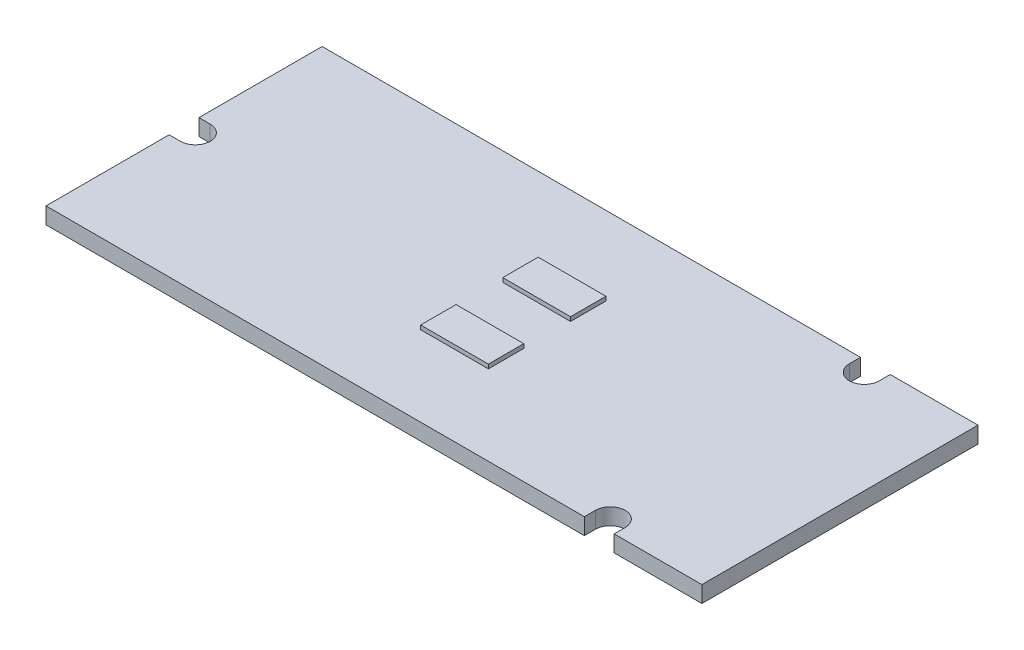
SolidWorks part; units mm, degrees
ref_plane "Front" through (0, 0, 0) normal (0, 0, 1) x (1, 0, 0)
ref_plane "Top" through (0, 0, 0) normal (0, 1, 0) x (1, 0, 0)
ref_plane "Right" through (0, 0, 0) normal (1, 0, 0) x (0, 0, -1)
sketch "Sketch1" plane through (0, 0, 0) normal (0, 1, 0) x (1, 0, 0)
  line L0 (-31.95, 0) -> (31.95, 0) construction
  line L1 (31.95, -13.45) -> (23.4, -13.45)
  line L2 (31.95, -13.45) -> (31.95, 13.45)
  line L3 (31.95, 13.45) -> (23.4, 13.45)
  line L4 (-31.95, -13.45) -> (-31.95, -1.45)
  line L5 (31.95, -13.45) -> (-31.95, 13.45) construction
  line L6 (31.95, 13.45) -> (-31.95, -13.45) construction
  line L7 (21.95, 13.7097) -> (21.95, -13.45) construction
  line L8 (20.5, 12.375) -> (20.5, 13.45)
  line L9 (23.4, 12.375) -> (23.4, 13.45)
  line L10 (20.5, 13.45) -> (-31.95, 13.45)
  line L11 (23.4, -12.375) -> (23.4, -13.45)
  line L12 (20.5, -12.375) -> (20.5, -13.45)
  line L13 (20.5, -13.45) -> (-31.95, -13.45)
  line L14 (-30.85, 1.45) -> (-31.95, 1.45)
  line L15 (-30.85, -1.45) -> (-31.95, -1.45)
  line L17 (-31.95, 1.45) -> (-31.95, 13.45)
  arc A0 (20.5, 12.375) -> (23.4, 12.375) centre (21.95, 12.375) ccw
  arc A1 (20.5, -12.375) -> (23.4, -12.375) centre (21.95, -12.375) cw
  arc A2 (-30.85, -1.45) -> (-30.85, 1.45) centre (-30.85, 0) ccw
  point P0 (0, 0)
  dimension "D4" = 2.9
  dimension "D5" = 24.75
  dimension "D6" = 2.9
  dimension "D7" = 52.8
  dimension "D1" = 63.9
  dimension "D2" = 26.9
  dimension "D3" = 10
extrude "Boss-Extrude1" add sketch "Sketch1" along normal blind 1.6
ref_plane "Plane1" through (21.95, 0, 0) normal (1, 0, 0) x (0, 0, -1)
sketch "Sketch2" plane through (0, 1.6, 0) normal (0, 1, 0) x (1, 0, 0)
  line L0 (20.5, 13.45) -> (-31.95, 13.45) construction
  line L1 (-3.25, 2.35) -> (3.35, 2.35)
  line L2 (-3.25, 2.35) -> (-3.25, 5.8)
  line L3 (-3.25, 5.8) -> (3.35, 5.8)
  line L4 (3.35, 2.35) -> (3.35, 5.8)
  line L5 (-3.25, 2.35) -> (3.35, 5.8) construction
  line L6 (-3.25, 5.8) -> (3.35, 2.35) construction
  line L7 (31.95, -13.45) -> (31.95, 13.45) construction
  line L8 (-3.25, -5.65) -> (3.35, -5.65)
  line L9 (-3.25, -5.65) -> (-3.25, -2.2)
  line L10 (-3.25, -2.2) -> (3.35, -2.2)
  line L11 (3.35, -5.65) -> (3.35, -2.2)
  line L12 (-3.25, -5.65) -> (3.35, -2.2) construction
  line L13 (-3.25, -2.2) -> (3.35, -5.65) construction
  point P0 (0.05, 4.075)
  point P9 (0.05, -3.925)
  dimension "D1" = 6.6
  dimension "D2" = 3.45
  dimension "D3" = 7.65
  dimension "D4" = 28.6
  dimension "D5" = 2
extrude "Boss-Extrude2" add sketch "Sketch2" along normal blind 0.4
